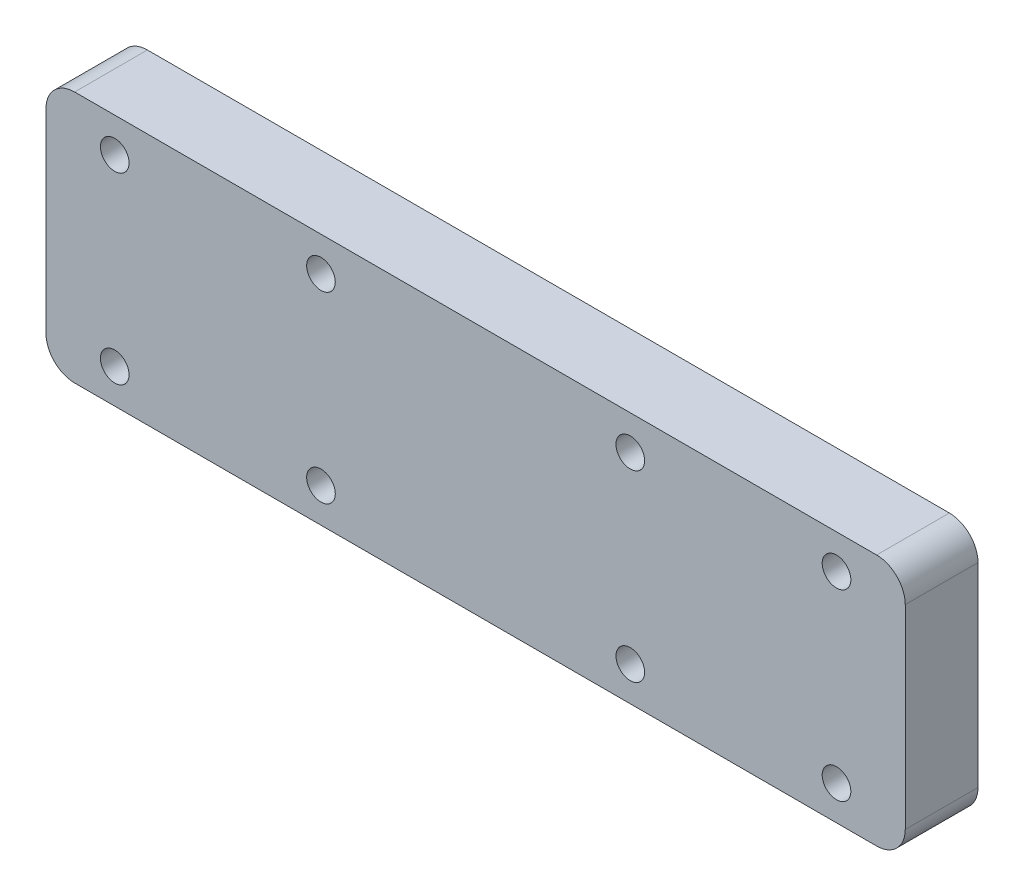
SolidWorks part; units mm, degrees
ref_plane "Front Plane" through (0, 0, 0) normal (0, 0, 1) x (1, 0, 0)
ref_plane "Top Plane" through (0, 0, 0) normal (0, 1, 0) x (1, 0, 0)
ref_plane "Right Plane" through (0, 0, 0) normal (1, 0, 0) x (0, 0, -1)
sketch "Sketch1" plane through (0, 0, 0) normal (0, 0, 1) x (1, 0, 0)
  line L0 (-27, 16) -> (-27, -16) construction
  line L1 (-27, 0) -> (0, 0) construction
  line L2 (75, 22) -> (-75, 22)
  line L3 (0, 22) -> (0, 0) construction
  line L4 (27, 16) -> (27, -16) construction
  line L5 (0, 0) -> (27, 0) construction
  line L6 (75, -22) -> (-75, -22)
  line L7 (-75, 22) -> (-75, -22)
  line L8 (75, 22) -> (75, -22)
  circle A0 centre (-63, -16) radius 2.5
  circle A1 centre (-63, 16) radius 2.5
  circle A2 centre (-27, -16) radius 2.5
  circle A3 centre (-27, 16) radius 2.5
  circle A4 centre (27, -16) radius 2.5
  circle A5 centre (27, 16) radius 2.5
  circle A6 centre (63, -16) radius 2.5
  circle A7 centre (63, 16) radius 2.5
  dimension "D7" = 5
  dimension "D1" = 36
  dimension "D2" = 32
  dimension "D3" = 90
  dimension "D4" = 36
  dimension "D6" = 150
  dimension "D5" = 44
extrude "Boss-Extrude1" add sketch "Sketch1" along normal blind 12.7
fillet "Fillet1" radius 5 4 edges at (75, 22, 6.35) (75, -22, 6.35) (-75, 22, 6.35) (-75, -22, 6.35)
sketch "Sketch2" plane through (0, 0, 0) normal (0, 0, -1) x (-1, 0, 0)
  line L0 (-75, -17) -> (-75, -87)
  line L2 (-75, -87) -> (-40, -87)
  line L3 (-40, -87) -> (-40, -22)
  line L4 (70, -22) -> (-70, -22) construction
  line L5 (-75, -81.2) -> (-40, -81.2) construction
  line L6 (-40, -22) -> (-70, -22)
  arc A0 (-75, -17) -> (-70, -22) centre (-70, -17) ccw construction
  arc A1 (-75, -17) -> (-70, -22) centre (-70, -17) ccw
  dimension "D1" = 5.8
  dimension "D2" = 35
  dimension "D3" = 65
extrude "Boss-Extrude2" [suppressed] add sketch "Sketch2" against normal up to surface (12.7 mm away) contours L0 L2 L3 L6 A1
sketch "Sketch3" [suppressed] plane through (0, 0, 0) normal (0, 0, -1) x (-1, 0, 0)
  line L0 (-75, -81.2) -> (-40, -81.2) construction
  line L1 (-57.5, -87) -> (-57.5, -22) construction
  line L2 (-75, -87) -> (-40, -87) construction
  line L3 (-40, -22) -> (-70, -22) construction
  circle A0 centre (-49.5, -81.2) radius 2.5 construction
  circle A1 centre (-65.5, -81.2) radius 2.5 construction
  circle A2 centre (-49.5, -31.3) radius 2.5 construction
  circle A3 centre (-65.5, -31.3) radius 2.5 construction
  dimension "D1" = 16
  dimension "D2" = 5
  dimension "D4" = 49.9
  dimension "D3" = 2
hole_wizard "M5x0.8 Tapped Hole1" [suppressed] positions "Sketch4" profile "Sketch5" tap size "M5x0.8" standard "ANSI Metric"
sketch "Sketch4" plane through (0, 0, 0) normal (0, 0, -1) x (-1, 0, 0)
  point P0 (-49.5, -31.3)
  point P3 (-65.5, -31.3)
  point P6 (-65.5, -81.2)
  point P9 (-49.5, -81.2)
sketch "Sketch5" plane through (49.5, -31.3, 0) normal (1, 0, 0) x (0, 1, 0)
  line L0 (0, 0) -> (0, 12.7)
  line L1 (0, 12.7) -> (2.1, 12.7)
  line L2 (2.1, 12.7) -> (2.1, 0)
  line L5 (2.1, 0) -> (0, 0)
  line L11 (0, -6.35) -> (0, 107.95) construction
  dimension "Thru Tap Drill Dia." = 4.2
  dimension "Thru Tap Drill Depth" = 12.7
cosmetic thread "Hole Thread1" [suppressed] parameters "D2"=5
cosmetic thread "Hole Thread2" [suppressed] parameters "D2"=5
cosmetic thread "Hole Thread3" [suppressed] parameters "D2"=5
cosmetic thread "Hole Thread4" [suppressed] parameters "D2"=5
sketch "Sketch6" [suppressed] plane through (0, 0, 0) normal (0, 0, -1) x (-1, 0, 0)
  line L0 (-40, -87) -> (-40, -22) construction
  line L1 (-67, -39.3) -> (-48, -39.3)
  line L2 (-67, -39.3) -> (-67, -73.2)
  line L3 (-67, -73.2) -> (-48, -73.2)
  line L4 (-48, -39.3) -> (-48, -73.2)
  line L5 (-57.5, -73.2) -> (-57.5, -39.3) construction
  line L6 (-67, -56.25) -> (-48, -56.25) construction
  line L7 (-75, -87) -> (-75, 17) construction
  circle A0 centre (-49.5, -31.3) radius 2.1 construction
  circle A1 centre (-49.5, -81.2) radius 2.1 construction
  point P140 (-57.5, -56.25)
  dimension "D4" = 8
  dimension "D1" = 8
  dimension "D2" = 8
  dimension "D3" = 8
extrude "Cut-Extrude1" [suppressed] cut sketch "Sketch6" against normal blind 9.7
sketch "Sketch7" plane through (0, 0, 0) normal (0, 0, -1) x (-1, 0, 0)
  line L0 (-27, 16) -> (27, 16) construction
  line L1 (-63, 16) -> (-27, 16) construction
  line L2 (-63, 16) -> (-63, -16) construction
  line L3 (-63, -16) -> (-27, -16) construction
  line L4 (-27, 16) -> (-27, -16) construction
  line L5 (-45, -16) -> (-45, 16) construction
  line L6 (-63, 0) -> (-27, 0) construction
  line L7 (27, 16) -> (63, 16) construction
  line L8 (27, 16) -> (27, -16) construction
  line L9 (27, -16) -> (63, -16) construction
  line L10 (63, 16) -> (63, -16) construction
  line L11 (45, -16) -> (45, 16) construction
  line L12 (27, 0) -> (63, 0) construction
  line L13 (-27, -16) -> (27, -16) construction
  line L14 (-58, 11) -> (-32, 11)
  line L15 (-32, 11) -> (-32, -11)
  line L16 (-58, -11) -> (-32, -11)
  line L17 (-58, 11) -> (-58, -11)
  line L18 (-22, 11) -> (22, 11)
  line L19 (22, 11) -> (22, -11)
  line L20 (-22, -11) -> (22, -11)
  line L21 (-22, 11) -> (-22, -11)
  line L22 (32, 11) -> (58, 11)
  line L23 (58, 11) -> (58, -11)
  line L24 (32, -11) -> (58, -11)
  line L25 (32, 11) -> (32, -11)
  point P110 (45, 0)
  point P144 (-45, 0)
  dimension "D1" = 5
  dimension "D2" = 5
  dimension "D3" = 5
extrude "Cut-Extrude2" cut sketch "Sketch7" against normal blind 9.7
fillet "Fillet2" [suppressed] radius 5
fillet "Fillet3" radius 5 12 edges at (-58, 11, 4.85) (-32, 11, 4.85) (-58, -11, 4.85) (-32, -11, 4.85) (-22, 11, 4.85) (-22, -11, 4.85) (22, -11, 4.85) (22, 11, 4.85) (32, 11, 4.85) (32, -11, 4.85) (58, -11, 4.85) (58, 11, 4.85)
equation "\"D4@Sketch1\"=\"D1@Sketch1\""
